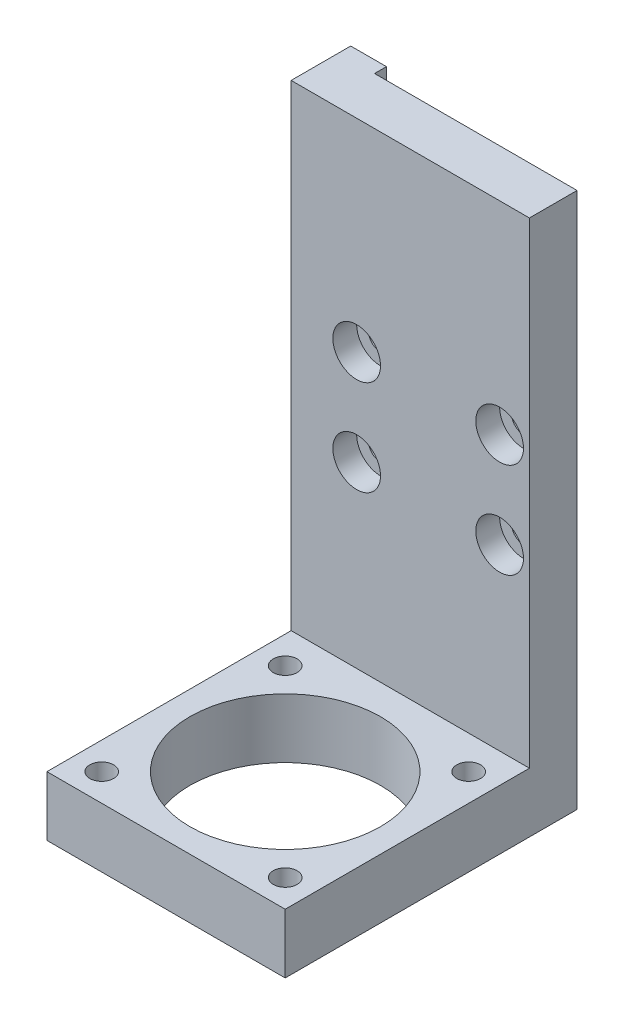
SolidWorks part; units mm, degrees
ref_plane "Front Plane" through (0, 0, 0) normal (0, 0, 1) x (1, 0, 0)
ref_plane "Top Plane" through (0, 0, 0) normal (0, 1, 0) x (1, 0, 0)
ref_plane "Right Plane" through (0, 0, 0) normal (1, 0, 0) x (0, 0, -1)
sketch "Sketch1" plane through (0, 0, 0) normal (1, 0, 0) x (0, 0, -1)
  line L0 (0, 0) -> (20.5, 0)
  line L1 (20.5, 0) -> (20.5, 40)
  line L2 (20.5, 40) -> (25.5, 40)
  line L3 (25.5, 40) -> (25.5, -5)
  line L4 (25.5, -5) -> (0, -5)
  line L5 (0, -5) -> (0, 0)
  dimension "D1" = 20.5
  dimension "D2" = 5
  dimension "D3" = 5
  dimension "D4" = 40
extrude "Boss-Extrude1" add sketch "Sketch1" along normal blind 20
sketch "Sketch3" plane through (0, 0, 0) normal (0, 1, 0) x (1, 0, 0)
  line L0 (20, 20.5) -> (20, 0) construction
  line L1 (20, 0) -> (0, 0) construction
  line L2 (0, 20.5) -> (0, 0) construction
  circle A0 centre (10, 10) radius 8
  circle A1 centre (2.3, 17.7) radius 1
  circle A2 centre (17.7, 17.7) radius 1
  circle A3 centre (17.7, 2.3) radius 1
  circle A4 centre (2.3, 2.3) radius 1
  dimension "D1" = 16
  dimension "D2" = 10
  dimension "D3" = 10
  dimension "D4" = 15.4
  dimension "D5" = 2
  dimension "D6" = 2
  dimension "D7" = 2
  dimension "D8" = 2
  dimension "D9" = 15.4
  dimension "D10" = 15.4
  dimension "D11" = 15.4
  dimension "D12" = 2.3
  dimension "D13" = 2.3
  dimension "D14" = 2.3
  dimension "D15" = 2.3
  dimension "D16" = 2.3
  dimension "D17" = 2.3
extrude "Cut-Extrude1" cut sketch "Sketch3" against normal blind 10
sketch "Sketch4" plane through (0, 0, -20.5) normal (0, 0, 1) x (1, 0, 0)
  line L1 (20, 0) -> (0, 0) construction
  line L2 (20, 40) -> (20, 0) construction
  circle A0 centre (5.5, 15) radius 1
  circle A1 centre (5.5, 23) radius 1
  circle A2 centre (17.5, 23) radius 1
  circle A3 centre (17.5, 15) radius 1
  dimension "D1" = 2
  dimension "D2" = 2
  dimension "D3" = 2
  dimension "D4" = 2
  dimension "D5" = 2.5
  dimension "D6" = 2.5
  dimension "D7" = 12
  dimension "D8" = 12
  dimension "D9" = 8
  dimension "D10" = 8
  dimension "D11" = 0
  dimension "D12" = 15
extrude "Cut-Extrude2" cut sketch "Sketch4" against normal blind 10
sketch "Sketch5" plane through (0, 0, -20.5) normal (0, 0, 1) x (1, 0, 0)
  circle A0 centre (5.5, 23) radius 2
  circle A1 centre (5.5, 15) radius 2
  circle A2 centre (17.5, 15) radius 2
  circle A3 centre (17.5, 23) radius 2
  dimension "D1" = 4
  dimension "D2" = 4
  dimension "D3" = 4
  dimension "D4" = 4
extrude "Cut-Extrude3" cut sketch "Sketch5" against normal blind 2
sketch "Sketch6" plane through (0, 40, 0) normal (0, 1, 0) x (1, 0, 0)
  line L6 (20, 25.5) -> (3, 25.5)
  line L7 (20, 25.5) -> (20, 24.5)
  line L8 (20, 24.5) -> (3, 24.5)
  line L9 (3, 25.5) -> (3, 24.5)
  dimension "D1" = 17
  dimension "D2" = 1
extrude "Cut-Extrude4" cut sketch "Sketch6" against normal blind 65
